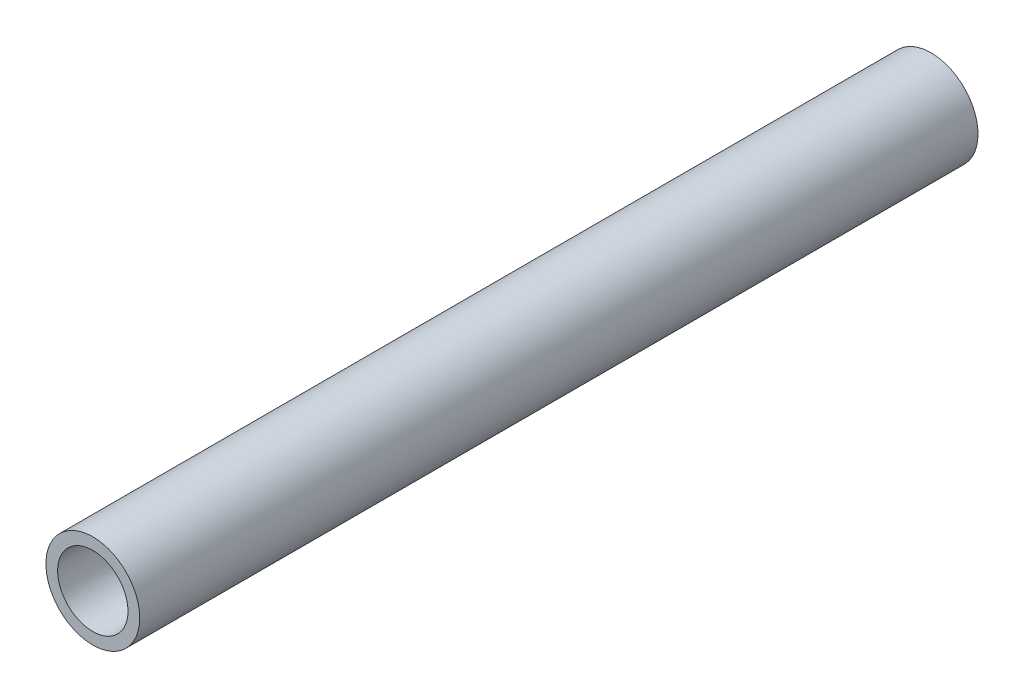
SolidWorks part; units mm, degrees
material "1060 Alloy"
ref_plane "Front Plane" through (0, 0, 0) normal (0, 0, 1) x (1, 0, 0)
ref_plane "Top Plane" through (0, 0, 0) normal (0, 1, 0) x (1, 0, 0)
ref_plane "Right Plane" through (0, 0, 0) normal (1, 0, 0) x (0, 0, -1)
sketch "Sketch1" plane through (0, 0, 0) normal (0, 0, 1) x (1, 0, 0)
  circle A0 centre (0, 0) radius 4
  dimension "D1" = 8
extrude "Extrude-Thin1" add sketch "Sketch1" along normal blind 71.5 thin thin type one direction reverse wall 1
